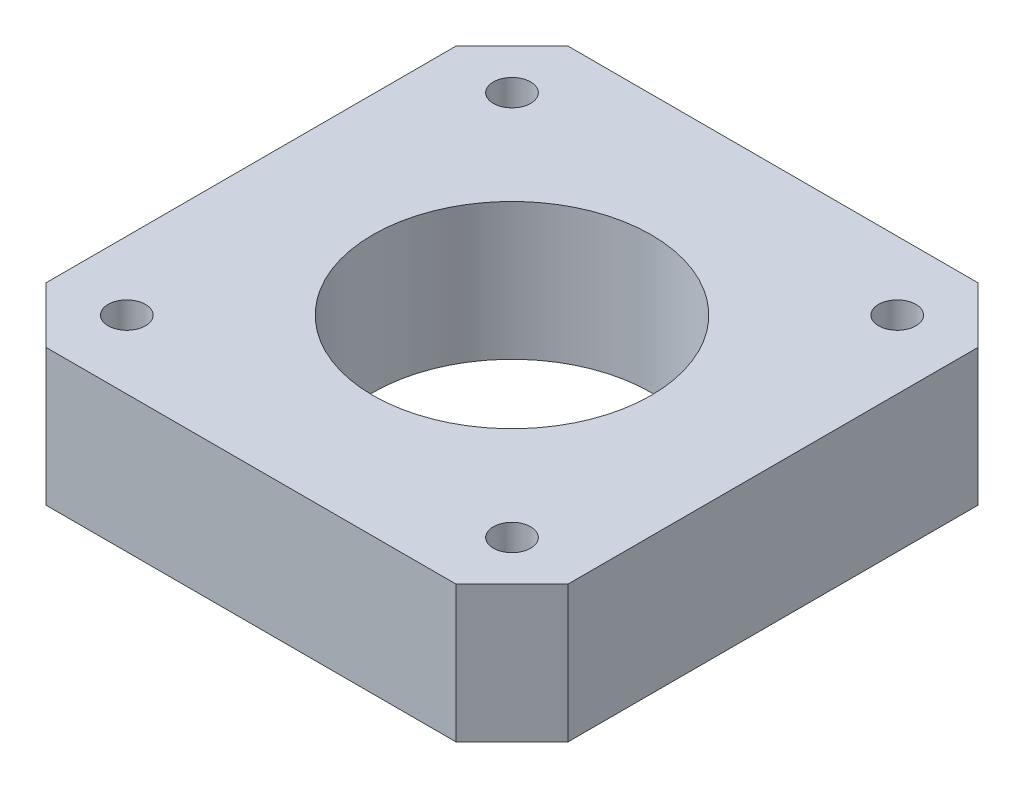
SolidWorks part; units mm, degrees
ref_plane "Front Plane" through (0, 0, 0) normal (0, 0, 1) x (1, 0, 0)
ref_plane "Top Plane" through (0, 0, 0) normal (0, 1, 0) x (1, 0, 0)
ref_plane "Right Plane" through (0, 0, 0) normal (1, 0, 0) x (0, 0, -1)
sketch "Sketch1" plane through (0, 0, 0) normal (0, 1, 0) x (1, 0, 0)
  line L1 (-21, -21) -> (21, -21)
  line L2 (-21, -21) -> (-21, 21)
  line L3 (-21, 21) -> (21, 21)
  line L4 (21, -21) -> (21, 21)
  line L5 (-21, -21) -> (21, 21) construction
  line L6 (-21, 21) -> (21, -21) construction
  point P0 (0, 0)
  dimension "D1" = 42
extrude "Boss-Extrude1" add sketch "Sketch1" along normal blind 11
chamfer "Chamfer1" distance 4.5 angle 45 4 edges at (-21, 5.5, -21) (21, 5.5, -21) (21, 5.5, 21) (-21, 5.5, 21)
sketch "Sketch3" plane through (0, 11, 0) normal (0, 1, 0) x (1, 0, 0)
  line L0 (0, -21) -> (0, 21) construction
  line L1 (16.5, 21) -> (-16.5, 21) construction
  line L2 (21, 0) -> (-21, 0) construction
  line L3 (-21, 16.5) -> (-21, -16.5) construction
  circle A0 centre (-15.5, 15.5) radius 1.5
  circle A1 centre (15.5, 15.5) radius 1.5
  circle A2 centre (15.5, -15.5) radius 1.5
  circle A3 centre (-15.5, -15.5) radius 1.5
  point P8 (0, 0)
  point P14 (0, 0)
  point P23 (0, 0)
  dimension "D1" = 3
  dimension "D2" = 31
  dimension "D3" = 31
  dimension "D4" = 4
extrude "Cut-Extrude1" cut sketch "Sketch3" against normal up to next
sketch "Sketch4" plane through (0, 11, 0) normal (0, 1, 0) x (1, 0, 0)
  circle A0 centre (0, 0) radius 11.2
  dimension "D1" = 22.4
extrude "Cut-Extrude2" cut sketch "Sketch4" against normal up to next
